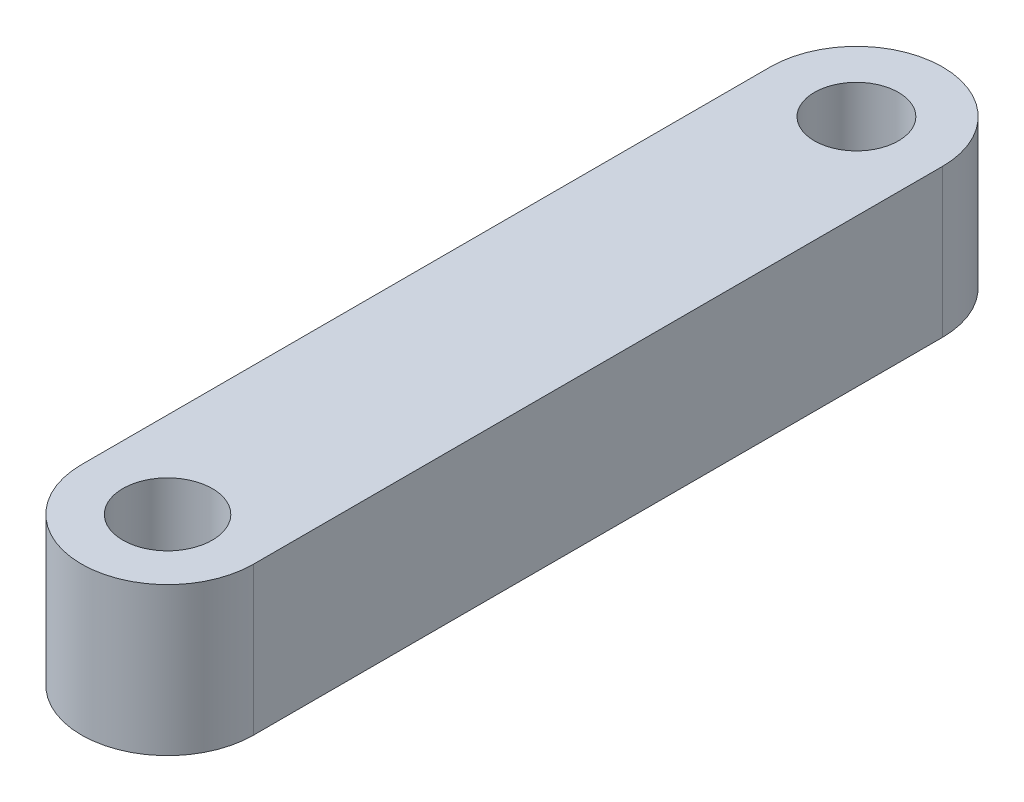
SolidWorks part; units mm, degrees
material "ABS"
ref_plane "Front Plane" through (0, 0, 0) normal (0, 0, 1) x (1, 0, 0)
ref_plane "Top Plane" through (0, 0, 0) normal (0, 1, 0) x (1, 0, 0)
ref_plane "Right Plane" through (0, 0, 0) normal (1, 0, 0) x (0, 0, -1)
sketch "Sketch1" plane through (0, 0, 0) normal (0, 1, 0) x (1, 0, 0)
  line L2 (-3.175, -12.7) -> (-3.175, 12.7)
  line L4 (3.175, -12.7) -> (3.175, 12.7)
  line L5 (-3.175, -12.7) -> (3.175, 12.7) construction
  line L6 (-3.175, 12.7) -> (3.175, -12.7) construction
  arc A0 (3.175, 12.7) -> (-3.175, 12.7) centre (0, 12.7) ccw
  arc A1 (-3.175, -12.7) -> (3.175, -12.7) centre (0, -12.7) ccw
  point P0 (0, 0)
  dimension "D1" = 25.4
  dimension "D3" = 6.35
extrude "Boss-Extrude1" add sketch "Sketch1" along normal blind 5.461
hole_wizard "M3 Clearance Hole clearance" positions "Sketch2" profile "Sketch3" hole size "M3" standard "ANSI Metric" end condition through all
sketch "Sketch2" plane through (0, 5.461, 0) normal (0, 1, 0) x (1, 0, 0)
  point P0 (0, -12.7)
sketch "Sketch3" plane through (0, 5.461, 12.7) normal (1, 0, 0) x (0, 0, 1)
  line L0 (0, 0) -> (0, 5.461)
  line L1 (0, 5.461) -> (1.65, 5.461)
  line L2 (1.65, 5.461) -> (1.65, 0)
  line L5 (1.65, 0) -> (0, 0)
  line L11 (0, -6.35) -> (0, 107.95) construction
  dimension "Thru Hole Dia." = 3.3
  dimension "Thru Hole Depth" = 5.461
hole_wizard "M3 Clearance Hole interference" positions "Sketch4" profile "Sketch5" hole size "M3" standard "ANSI Metric" end condition through all
sketch "Sketch4" plane through (0, 5.461, 0) normal (0, 1, 0) x (1, 0, 0)
  point P0 (0, 12.7)
sketch "Sketch5" plane through (0, 5.461, -12.7) normal (1, 0, 0) x (0, 0, 1)
  line L0 (0, 0) -> (0, 5.461)
  line L1 (0, 5.461) -> (1.55, 5.461)
  line L2 (1.55, 5.461) -> (1.55, 0)
  line L5 (1.55, 0) -> (0, 0)
  line L11 (0, -6.35) -> (0, 107.95) construction
  dimension "Thru Hole Dia." = 3.1
  dimension "Thru Hole Depth" = 5.461
equation "\"Arm_Length\"= 1"
equation "\"D1@Sketch1\"=\"Arm_Length\""
